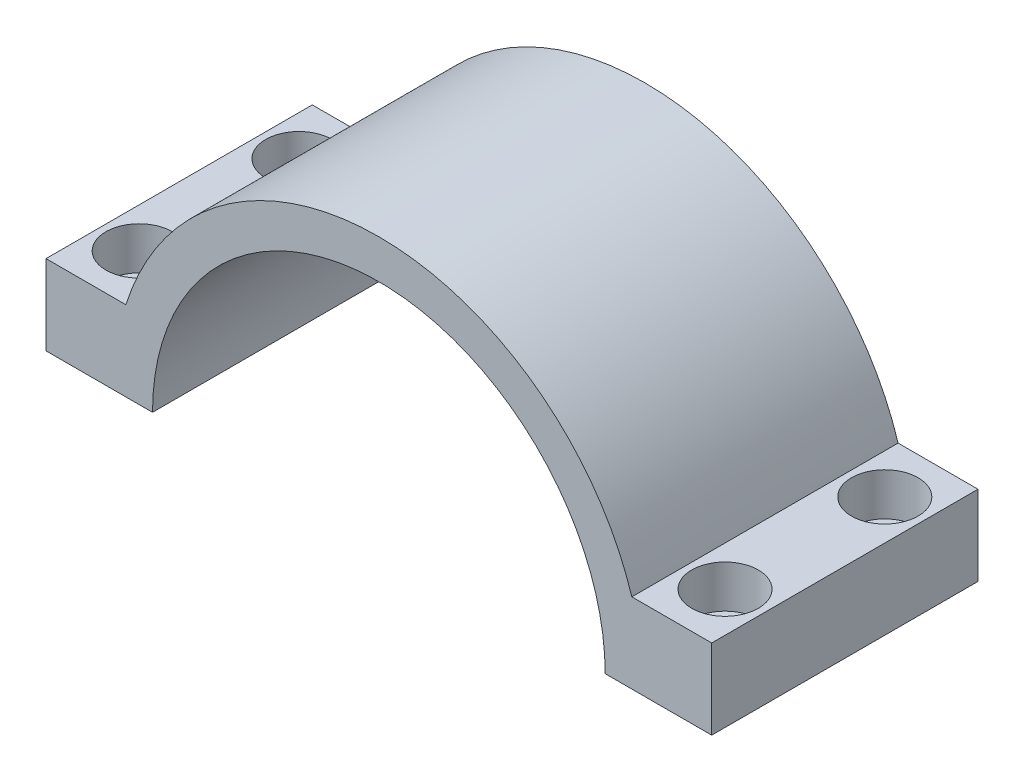
SolidWorks part; units mm, degrees
ref_plane "Alzado" through (0, 0, 0) normal (0, 0, 1) x (1, 0, 0)
ref_plane "Planta" through (0, 0, 0) normal (0, 1, 0) x (1, 0, 0)
ref_plane "Vista lateral" through (0, 0, 0) normal (1, 0, 0) x (0, 0, -1)
sketch "Croquis1" plane through (0, 0, 0) normal (0, 0, 1) x (1, 0, 0)
  line L0 (0, 0) -> (-8.5, 0) construction
  line L1 (-8.5, 0) -> (8.5, 0) construction
  line L2 (-8.5, 0) -> (-12.5, 0)
  line L3 (-12.5, 0) -> (-12.5, 3)
  line L4 (-12.5, 3) -> (-9.5, 3)
  line L5 (0, 0) -> (0, 5.9199) construction
  line L6 (12.5, 0) -> (12.5, 3)
  line L7 (8.5, 0) -> (12.5, 0)
  line L8 (12.5, 3) -> (9.5, 3)
  arc A0 (8.5, 0) -> (-8.5, 0) centre (0, 0) ccw
  arc A1 (-9.5, 3) -> (9.5, 3) centre (0, 0) cw
  dimension "D1" = 17
  dimension "D2" = 4
  dimension "D3" = 3
  dimension "D4" = 3
extrude "Saliente-Extruir1" add sketch "Croquis1" along normal blind 10 contours A1 L4 L3 L2 A0 L7 L6 L8
sketch "Croquis2" plane through (0, 3, 0) normal (0, 1, 0) x (1, 0, 0)
  line L0 (-12.5, 0) -> (-9.5, 0) construction
  line L1 (-11, 0) -> (-11, -10)
  line L2 (-12.5, -10) -> (-9.5, -10) construction
  line L3 (-12.5, -10) -> (-12.5, 0) construction
  line L4 (0, 0) -> (0, -12.6545) construction
  point P6 (-11, -8)
  point P7 (-11, -2)
  point P8 (-11, -5)
  point P14 (11, -8)
  point P15 (11, -2)
  dimension "D1" = 3
  dimension "D2" = 3
  dimension "D3" = 1.5
hole_wizard "Refrentado para tornillo con cabeza troncocónica de M23" positions "Croquis3D1" profile "Croquis4" counterbore size "M2" standard "Ansi Metric" end condition through all
sketch3d "Croquis3D1"
  point P0 (-11, 3, 2)
  point P4 (-11, 3, 8)
  point P7 (11, 3, 2)
  point P10 (11, 3, 8)
sketch "Croquis4" plane through (-11, 3, 2) normal (1, 0, 0) x (0, 0, 1)
  line L0 (0, 0) -> (0, 3)
  line L1 (0, 3) -> (1, 3)
  line L3 (1, 3) -> (1, 1.6)
  line L4 (1, 1.6) -> (1.25, 1.6)
  line L5 (1.25, 1.6) -> (1.25, 0)
  line L7 (1.25, 0) -> (0, 0)
  line L11 (0, -6.35) -> (0, 107.95) construction
  dimension "Diámetro de taladro hasta el siguiente" = 2
  dimension "Profundidad de taladro hasta el siguiente" = 3
  dimension "Diámetro de refrentado" = 2.5
  dimension "Profundidad de refrentado" = 1.6
